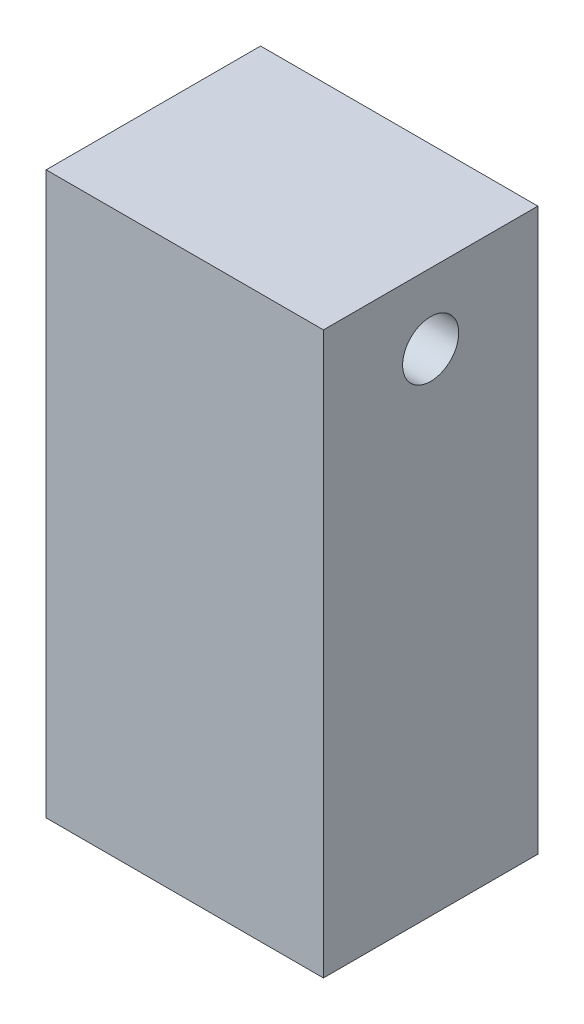
SolidWorks part; units mm, degrees
ref_plane "Front Plane" through (0, 0, 0) normal (0, 0, 1) x (1, 0, 0)
ref_plane "Top Plane" through (0, 0, 0) normal (0, 1, 0) x (1, 0, 0)
ref_plane "Right Plane" through (0, 0, 0) normal (1, 0, 0) x (0, 0, -1)
sketch "Sketch1" plane through (0, 0, 0) normal (0, 1, 0) x (1, 0, 0)
  line L0 (0, 0) -> (0, -5.3277) construction
  line L1 (1.5685, 1.2129) -> (-1.5684, 1.2128)
  line L2 (1.5685, 1.2129) -> (1.5685, -1.2128)
  line L3 (1.5685, -1.2128) -> (-1.5684, -1.2128)
  line L4 (-1.5684, 1.2128) -> (-1.5684, -1.2128)
  line L5 (1.5685, 1.2129) -> (-1.5684, -1.2128) construction
  line L6 (1.5685, -1.2128) -> (-1.5684, 1.2128) construction
  point P0 (0, 0)
  dimension "D1" = 3.1369
  dimension "D2" = 2.4257
extrude "Boss-Extrude1" add sketch "Sketch1" along normal blind 6.35
sketch "Sketch2" plane through (-1.5684, 0, 0.3556) normal (1, 0, 0) x (0, 0, -1)
  line L0 (0.3556, 0) -> (0.3556, 6.35) construction
  line L3 (1.5684, 6.35) -> (-0.8573, 6.35) construction
  line L4 (1.5684, 0) -> (-0.8573, 0) construction
  circle A0 centre (0.3556, 5.5562) radius 0.3175
  point P4 (0.3556, 0)
  point P8 (0, 0)
  point P9 (0, 6.35)
  point P15 (0.3064, 6.35)
  dimension "D1" = 0.635
  dimension "D2" = 0.7938
extrude "Cut-Extrude1" cut sketch "Sketch2" along normal through all
